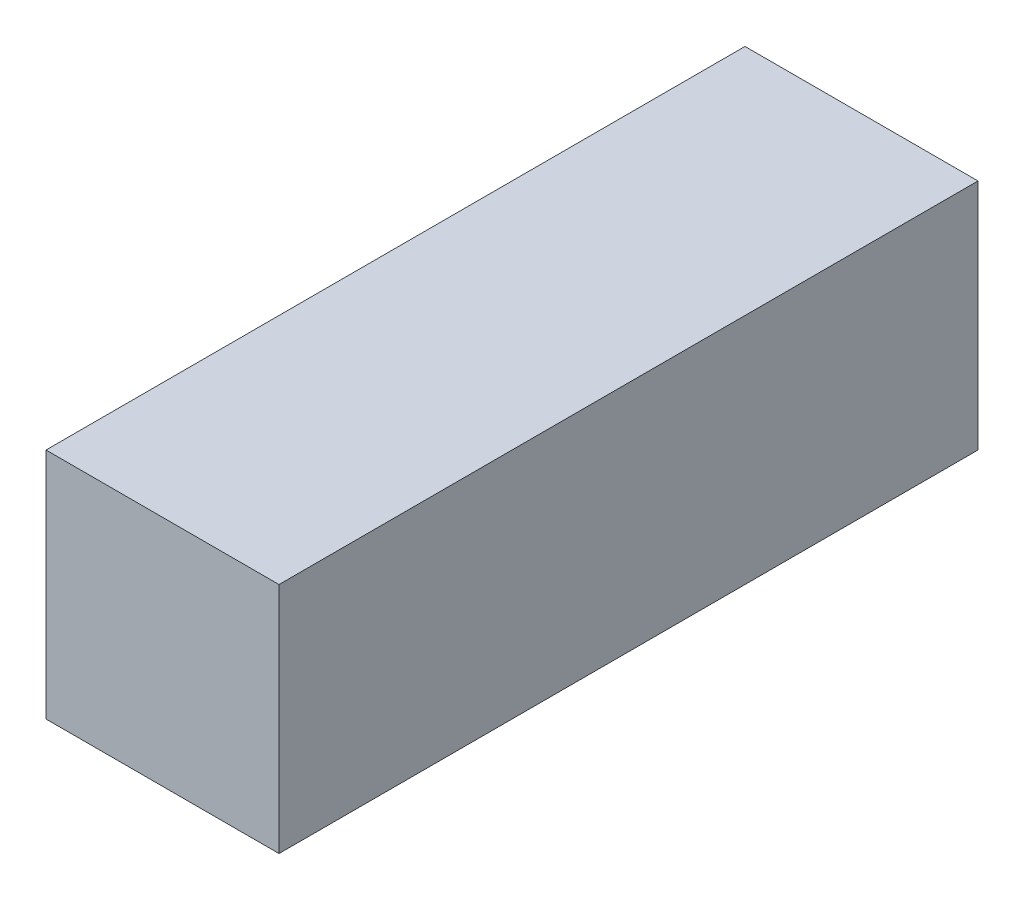
SolidWorks part; units mm, degrees
ref_plane "前视基准面" through (0, 0, 0) normal (0, 0, 1) x (1, 0, 0)
ref_plane "上视基准面" through (0, 0, 0) normal (0, 1, 0) x (1, 0, 0)
ref_plane "右视基准面" through (0, 0, 0) normal (1, 0, 0) x (0, 0, -1)
other "Configuration Table"
sketch "草图1" plane through (0, 0, 0) normal (0, 0, 1) x (1, 0, 0)
  line L1 (0, 0) -> (10, 0)
  line L2 (0, 0) -> (0, 10)
  line L3 (0, 10) -> (10, 10)
  line L4 (10, 0) -> (10, 10)
extrude "凸台-拉伸1" add sketch "草图1" along normal blind 30
